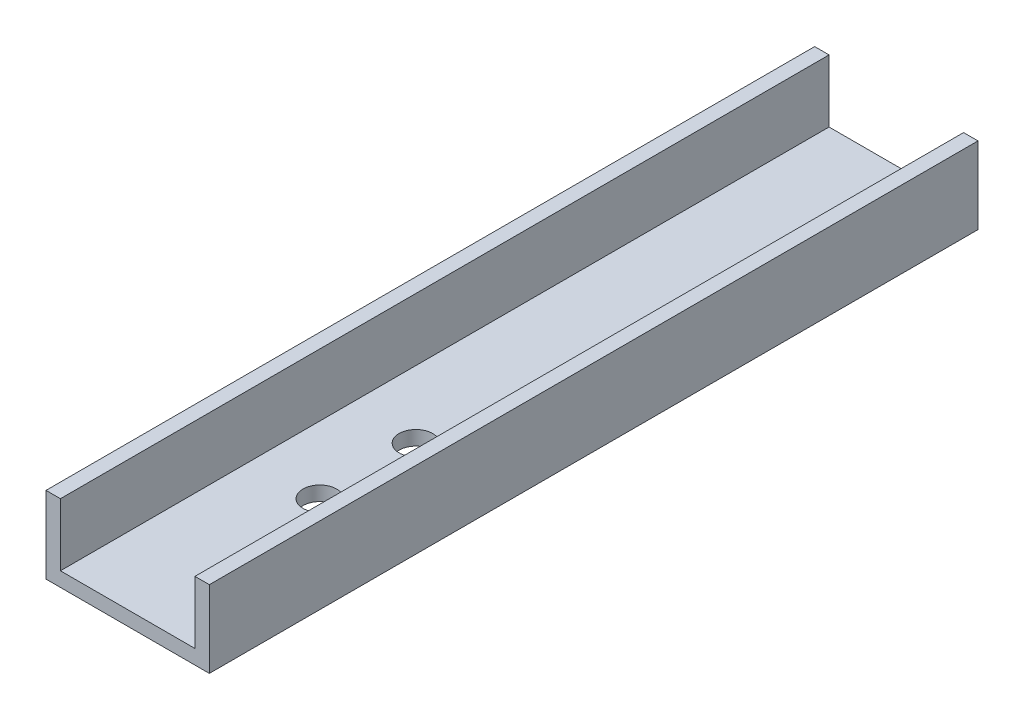
SolidWorks part; units mm, degrees
ref_plane "正面" through (0, 0, 0) normal (0, 0, 1) x (1, 0, 0)
ref_plane "平面" through (0, 0, 0) normal (0, 1, 0) x (1, 0, 0)
ref_plane "右側面" through (0, 0, 0) normal (1, 0, 0) x (0, 0, -1)
sketch "ｽｹｯﾁ1" plane through (0, 0, 0) normal (0, 0, 1) x (1, 0, 0)
  line L0 (0, 0) -> (-7, 0)
  line L1 (-7, 0) -> (-7, 6.5)
  line L2 (-7, 6.5) -> (-8.5, 6.5)
  line L3 (-8.5, 6.5) -> (-8.5, -1.5)
  line L4 (-8.5, -1.5) -> (8.5, -1.5)
  line L5 (8.5, -1.5) -> (8.5, 6.5)
  line L6 (8.5, 6.5) -> (7, 6.5)
  line L7 (7, 6.5) -> (7, 0)
  line L8 (7, 0) -> (0, 0)
  dimension "D1" = 17
  dimension "D2" = 8
  dimension "D3" = 8
  dimension "D4" = 1.5
  dimension "D5" = 1.5
  dimension "D6" = 1.5
  dimension "D7" = 7
extrude "ﾎﾞｽ - 押し出し1" add sketch "ｽｹｯﾁ1" along normal blind 80
sketch "ｽｹｯﾁ2" plane through (0, -1.5, 0) normal (0, -1, 0) x (1, 0, 0)
  line L1 (-8.5, 80) -> (-8.5, 0) construction
  line L2 (-8.5, 0) -> (8.5, 0) construction
  circle A0 centre (0, 50) radius 1.75
  circle A1 centre (0, 60) radius 1.75
  dimension "D1" = 3.5
  dimension "D2" = 50
  dimension "D3" = 3.5
  dimension "D5" = 8.5
  dimension "D4" = 10
extrude "ｶｯﾄ - 押し出し1" cut sketch "ｽｹｯﾁ2" against normal through all
